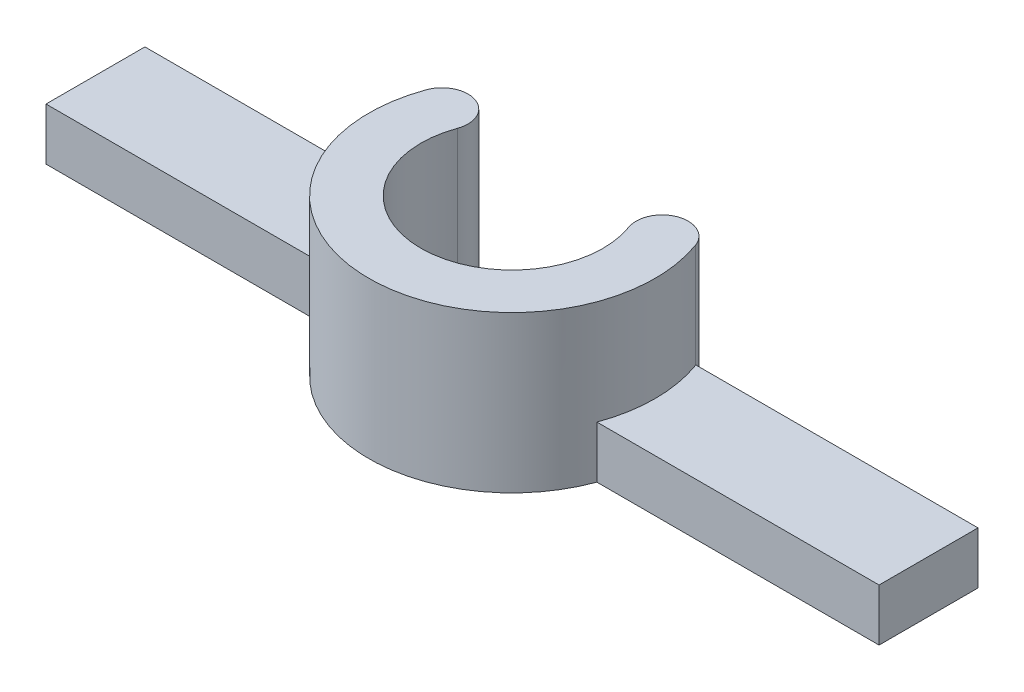
SolidWorks part; units mm, degrees
ref_plane "Front Plane" through (0, 0, 0) normal (0, 0, 1) x (1, 0, 0)
ref_plane "Top Plane" through (0, 0, 0) normal (0, 1, 0) x (1, 0, 0)
ref_plane "Right Plane" through (0, 0, 0) normal (1, 0, 0) x (0, 0, -1)
sketch "Sketch1" plane through (0, 0, 0) normal (0, 1, 0) x (1, 0, 0)
  line L0 (0, 0) -> (5.5, 0)
  line L1 (0, 0) -> (5.1683, 1.8811)
  line L2 (5.1683, 1.8811) -> (4.2286, 1.5391)
  line L3 (0, -55) -> (0, 55) construction
  circle A0 centre (0, 0) radius 3.5
  circle A1 centre (0, 0) radius 5.5
  arc A2 (5.1683, 1.8811) -> (3.2889, 1.1971) centre (4.2286, 1.5391) ccw
  arc A3 (-5.1683, 1.8811) -> (-3.2889, 1.1971) centre (-4.2286, 1.5391) cw
  dimension "D1" = 7
  dimension "D2" = 11
  dimension "D3" = 20
  dimension "D4" = 1
extrude "Boss-Extrude1" add sketch "Sketch1" along normal blind 6 contours A3 A1 L0 A0 | L0 A1 L1 A0 | L1 A2
sketch "Sketch2" plane through (0, 0, 0) normal (0, 1, 0) x (1, 0, 0)
  line L0 (0, 0) -> (16, 0)
  line L1 (-3.3, 0) -> (3.3, 0) construction
  line L2 (16, 0) -> (16, 1.9)
  line L3 (0, -3.3) -> (0, 3.3) construction
  line L4 (16, 1.9) -> (4.5, 1.9)
  line L5 (16, 1.9) -> (16, -1.9)
  line L6 (16, -1.9) -> (4.5, -1.9)
  line L7 (4.5, 1.9) -> (4.5, -1.9)
  line L8 (-16, -1.9) -> (-4.5, -1.9)
  line L9 (-4.5, 1.9) -> (-4.5, -1.9)
  line L10 (-16, 1.9) -> (-4.5, 1.9)
  line L11 (-16, 1.9) -> (-16, -1.9)
  dimension "D1" = 16
  dimension "D2" = 1.9
  dimension "D3" = 3.8
  dimension "D4" = 11.5
extrude "Boss-Extrude2" add sketch "Sketch2" along normal blind 2 contours L10 L11 L8 L9 | L0 L7 L6 L5 | L4 L7 L0 L2
